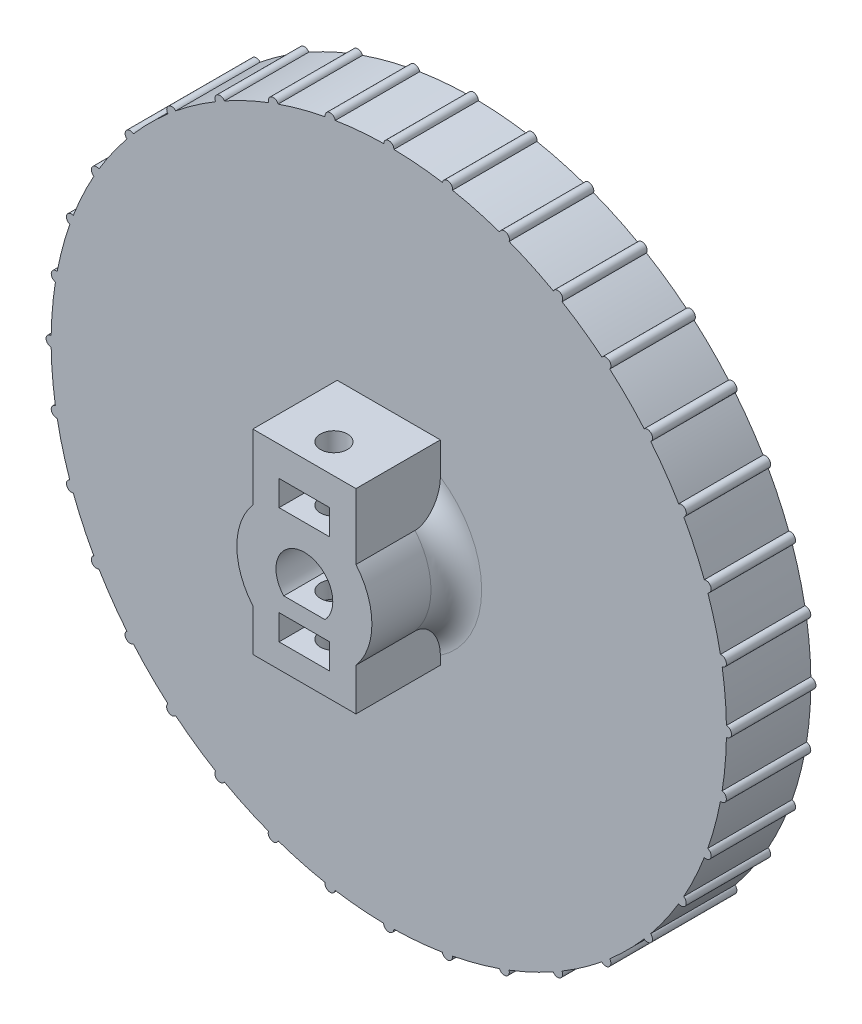
SolidWorks part; units mm, degrees
ref_plane "Ön Düzlem" through (0, 0, 0) normal (0, 0, 1) x (1, 0, 0)
ref_plane "Üst Düzlem" through (0, 0, 0) normal (0, 1, 0) x (1, 0, 0)
ref_plane "Sağ Düzlem" through (0, 0, 0) normal (1, 0, 0) x (0, 0, -1)
sketch "Çizim1" plane through (0, 0, 0) normal (0, 0, 1) x (1, 0, 0)
  line L0 (-1.9, -2.3216) -> (1.9, -2.3216)
  arc A0 (1.9, -2.3216) -> (-1.9, -2.3216) centre (0, 0) ccw
  circle A1 centre (0, 0) radius 8
  circle A2 centre (0, 0) radius 3 construction
  dimension "D1" = 6
  dimension "D3" = 3.8
  dimension "D2" = 5
extrude "Yükseklik-Ekstrüzyon1" add sketch "Çizim1" along normal blind 8
sketch "Çizim3" plane through (0, 0, 8) normal (0, 0, 1) x (1, 0, 0)
  line L0 (-1.9, -2.3216) -> (1.9, -2.3216) construction
  line L1 (-3, -4.3216) -> (3, -4.3216)
  line L2 (-3, -4.3216) -> (-3, -7.3216)
  line L3 (-3, -7.3216) -> (3, -7.3216)
  line L4 (3, -4.3216) -> (3, -7.3216)
  line L5 (-3, -4.3216) -> (3, -7.3216) construction
  line L6 (-3, -7.3216) -> (3, -4.3216) construction
  point P0 (0, -5.8216)
  point P8 (0, -2.3216)
  dimension "D1" = 6
  dimension "D2" = 3
  dimension "D3" = 2
extrude "Kes-Ekstrüzyon1" cut sketch "Çizim3" against normal blind 7
sketch "Çizim4" plane through (0, 0, 0) normal (0, 0, -1) x (-1, 0, 0)
  line L0 (1.9, -2.3216) -> (-1.9, -2.3216) construction
  line L1 (1.9, -2.3216) -> (-1.9, -2.3216)
  arc A0 (1.9, -2.3216) -> (-1.9, -2.3216) centre (0, 0) ccw construction
  circle A1 centre (0, 0) radius 8
  circle A2 centre (0, 0) radius 8
  arc A3 (1.9, -2.3216) -> (-1.9, -2.3216) centre (0, 0) ccw
  dimension "D1" = 0
extrude "Yükseklik-Ekstrüzyon2" add sketch "Çizim4" along normal blind 2
sketch "Çizim5" plane through (0, -4.3216, 0) normal (0, -1, 0) x (1, 0, 0)
  line L0 (3, 8) -> (-3, 8) construction
  circle A0 centre (0, 4.5) radius 1.6
  dimension "D1" = 3.2
  dimension "D2" = 3.5
extrude "Kes-Ekstrüzyon2" cut sketch "Çizim5" against normal blind 2 and the other way blind 7
sketch "Çizim6" plane through (0, 0, -2) normal (0, 0, -1) x (-1, 0, 0)
  circle A0 centre (0, 0) radius 40
  dimension "D1" = 80
extrude "Yükseklik-Ekstrüzyon3" add sketch "Çizim6" along normal blind 10
fillet "Radyus1" radius 3 1 edges at (-8, 0, -2)
sketch "Çizim9" plane through (0, 0, -2) normal (0, 0, 1) x (1, 0, 0)
  circle A0 centre (0, 0) radius 40
  arc A1 (-0.5949, 39.9956) -> (0.6076, 39.9954) centre (0.0063, 39.9955) cw
extrude "Yükseklik-Ekstrüzyon4" add sketch "Çizim9" against normal up to surface (10 mm away) contours A1
pattern_circular "Dairesel Kaplama1" count 36 every 10 about axis through (0, 0, 0) along (0, 0, 1) of "Yükseklik-Ekstrüzyon4"
sketch "Çizim10" plane through (0, 0, -2) normal (0, 0, 1) x (1, 0, 0)
  line L1 (-1.9, -2.3216) -> (1.9, -2.3216)
  line L2 (-1.9, -2.3216) -> (1.9, -2.3216)
  arc A1 (1.9, -2.3216) -> (-1.9, -2.3216) centre (0, 0) ccw
  arc A2 (1.9, -2.3216) -> (-1.9, -2.3216) centre (0, 0) ccw
  dimension "D1" = 0
extrude "Kes-Ekstrüzyon3" cut sketch "Çizim10" against normal blind 19
sketch "Çizim11" plane through (0, 0, 8) normal (0, 0, 1) x (1, 0, 0)
  line L0 (-3, -4.3216) -> (-3, -7.3216) construction
  line L1 (-6.1093, -5.1649) -> (-3, -5.1649)
  line L2 (-6.1093, -5.1649) -> (-6.1093, -10.1649)
  line L3 (-6.1093, -10.1649) -> (6.1093, -10.1649)
  line L4 (6.1093, -5.1649) -> (6.1093, -10.1649)
  line L5 (3, -7.3216) -> (3, -4.3216) construction
  line L6 (-3, -7.3216) -> (3, -7.3216) construction
  line L7 (3, -7.3216) -> (3, -4.3216)
  line L8 (-3, -4.3216) -> (-3, -7.3216)
  line L9 (-3, -7.3216) -> (3, -7.3216)
  line L10 (3, -5.1649) -> (6.1093, -5.1649)
  line L11 (3, -5.1649) -> (3, -7.3216)
  line L12 (-3, -7.3216) -> (-3, -5.1649)
  line L13 (3, -7.3216) -> (-3, -7.3216)
  circle A0 centre (0, 0) radius 8 construction
  line M3 (3, -7.3216) -> (-3, -7.3216)
  line M4 (-3, -7.3216) -> (-3, -4.3216)
  circle M6 centre (0, 0) radius 8
  dimension "D1" = 5
extrude "Yükseklik-Ekstrüzyon5" add sketch "Çizim11" against normal up to surface (10 mm away) contours L4 L2 L3 M6 | L10 L7 L1 M3 M4 M6
sketch "Çizim12" plane through (0, -2.3216, 0) normal (0, 1, 0) x (1, 0, 0)
  circle A0 centre (0, -4.5) radius 1.6 construction
  circle A1 centre (0, -4.5) radius 1.6
extrude "Kes-Ekstrüzyon4" cut sketch "Çizim12" against normal blind 19
sketch "Çizim13" plane through (0, 0, 8) normal (0, 0, 1) x (1, 0, 0)
  line L0 (2.4369, -2.3216) -> (-2.4369, -2.3216)
  arc A0 (2.4369, -2.3216) -> (-2.4369, -2.3216) centre (0, 0) ccw
extrude "Kes-Ekstrüzyon5" cut sketch "Çizim13" against normal blind 72
sketch "Çizim14" plane through (0, 0, 8) normal (0, 0, 1) x (1, 0, 0)
  line L1 (-6.1093, 5.1649) -> (6.1093, 5.1649)
  line L2 (-6.1093, 5.1649) -> (-6.1093, 12.9566)
  line L3 (-6.1093, 12.9566) -> (6.1093, 12.9566)
  line L4 (6.1093, 5.1649) -> (6.1093, 12.9566)
  arc A0 (6.1093, -5.1649) -> (-6.1093, -5.1649) centre (0, 0) ccw construction
extrude "Yükseklik-Ekstrüzyon6" add sketch "Çizim14" against normal blind 14
sketch "Çizim15" plane through (0, 0, 8) normal (0, 0, 1) x (1, 0, 0)
  line L1 (-3, 9.4448) -> (3, 9.4448)
  line L2 (-3, 9.4448) -> (-3, 6.4448)
  line L3 (-3, 6.4448) -> (3, 6.4448)
  line L4 (3, 9.4448) -> (3, 6.4448)
  line L6 (6.1093, 5.1649) -> (6.1093, 12.9566)
  line L7 (6.1093, 12.9566) -> (-6.1093, 12.9566)
  line L8 (-6.1093, 12.9566) -> (-6.1093, 5.1649)
  line L9 (-6.1093, -5.1649) -> (-6.1093, -10.1649)
  line L10 (-6.1093, -10.1649) -> (6.1093, -10.1649)
  line L11 (6.1093, -10.1649) -> (6.1093, -5.1649)
  line L13 (6.1093, 12.9566) -> (-6.1093, 12.9566)
  line L14 (-6.1093, 12.9566) -> (-6.1093, 5.1649)
  line L15 (-6.1093, -5.1649) -> (-6.1093, -10.1649)
  line L16 (-6.1093, -10.1649) -> (6.1093, -10.1649)
  line L17 (6.1093, -10.1649) -> (6.1093, -5.1649)
  arc A2 (6.1093, -5.1649) -> (6.1093, 5.1649) centre (0, 0) ccw
  arc A3 (-6.1093, 5.1649) -> (-6.1093, -5.1649) centre (0, 0) ccw
  arc A4 (6.1093, -5.1649) -> (6.1093, 5.1649) centre (0, 0) ccw
  arc A5 (-6.1093, 5.1649) -> (-6.1093, -5.1649) centre (0, 0) ccw
  dimension "D2" = 3
  dimension "D1" = 0
extrude "Kes-Ekstrüzyon6" cut sketch "Çizim15" against normal blind 7 contours L4 L1 L2 L3
sketch "Çizim16" plane through (0, -10.1649, 0) normal (0, -1, 0) x (1, 0, 0)
  circle A0 centre (0, 4.5) radius 1.6 construction
  circle A1 centre (0, 4.5) radius 1.6
extrude "Kes-Ekstrüzyon7" cut sketch "Çizim16" against normal blind 40
